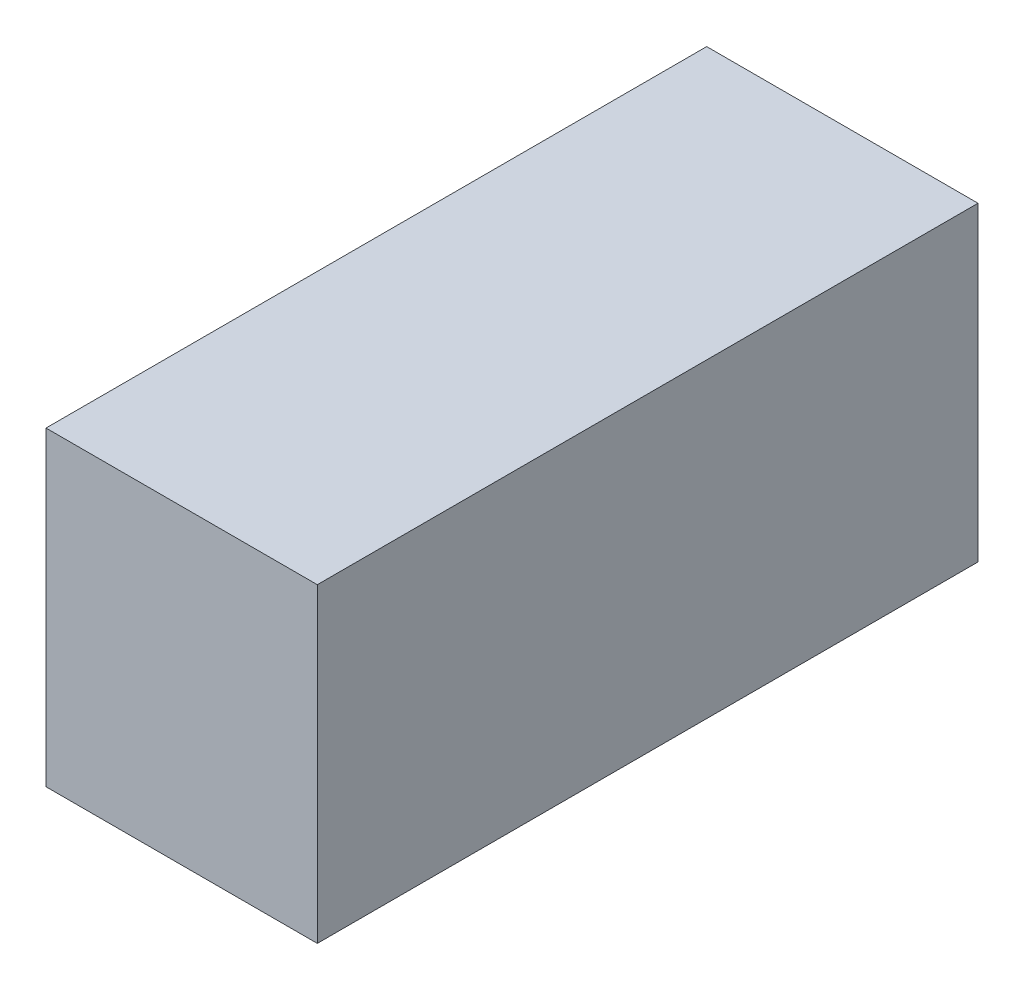
SolidWorks part; units mm, degrees
ref_plane "Front Plane" through (0, 0, 0) normal (0, 0, 1) x (1, 0, 0)
ref_plane "Top Plane" through (0, 0, 0) normal (0, 1, 0) x (1, 0, 0)
ref_plane "Right Plane" through (0, 0, 0) normal (1, 0, 0) x (0, 0, -1)
sketch "Sketch1" plane through (0, 0, 0) normal (0, 0, 1) x (1, 0, 0)
  line L1 (-58.6053, 33.6118) -> (72.3947, 33.6118)
  line L2 (-58.6053, 33.6118) -> (-58.6053, -116.3882)
  line L3 (-58.6053, -116.3882) -> (72.3947, -116.3882)
  line L4 (72.3947, 33.6118) -> (72.3947, -116.3882)
  dimension "D1" = 131
  dimension "D2" = 150
extrude "Boss-Extrude1" add sketch "Sketch1" along normal blind 319
